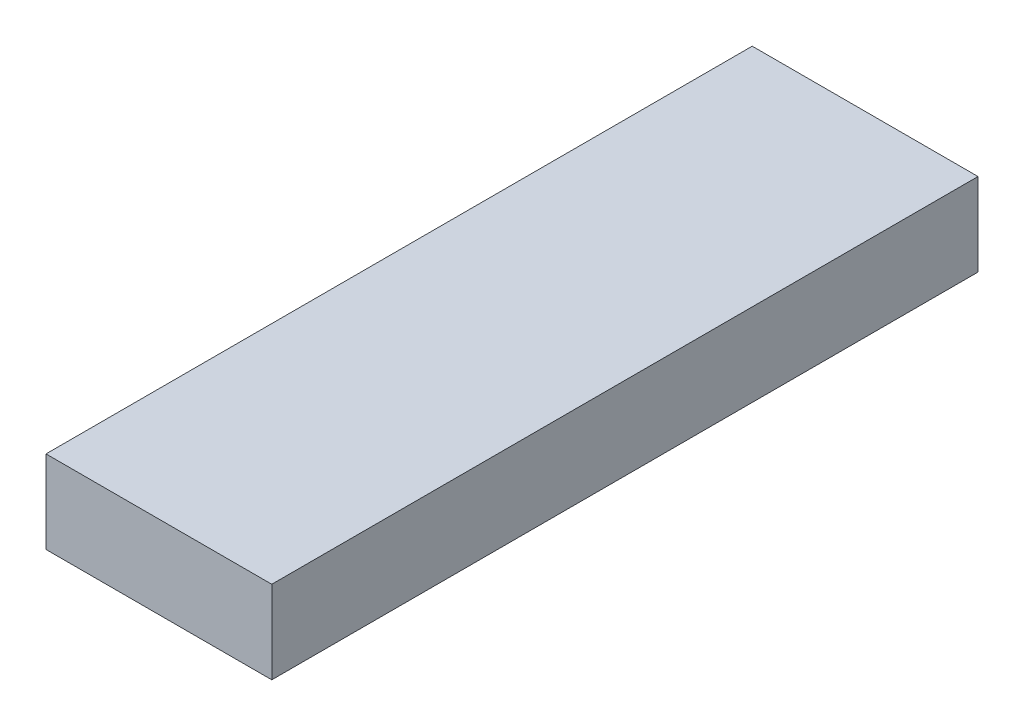
SolidWorks part; units mm, degrees
ref_plane "Front Plane" through (0, 0, 0) normal (0, 0, 1) x (1, 0, 0)
ref_plane "Top Plane" through (0, 0, 0) normal (0, 1, 0) x (1, 0, 0)
ref_plane "Right Plane" through (0, 0, 0) normal (1, 0, 0) x (0, 0, -1)
sketch "Sketch1" plane through (0, 0, 0) normal (0, 1, 0) x (1, 0, 0)
  line L1 (0, 0) -> (381, 0)
  line L2 (0, 0) -> (0, 1191.768)
  line L3 (0, 1191.768) -> (381, 1191.768)
  line L4 (381, 0) -> (381, 1191.768)
  dimension "D1" = 1191.768
  dimension "D2" = 381
extrude "Boss-Extrude1" add sketch "Sketch1" along normal blind 139.7
ref_plane "Plane1" through (0, 69.85, 0) normal (0, 1, 0) x (1, 0, 0)
